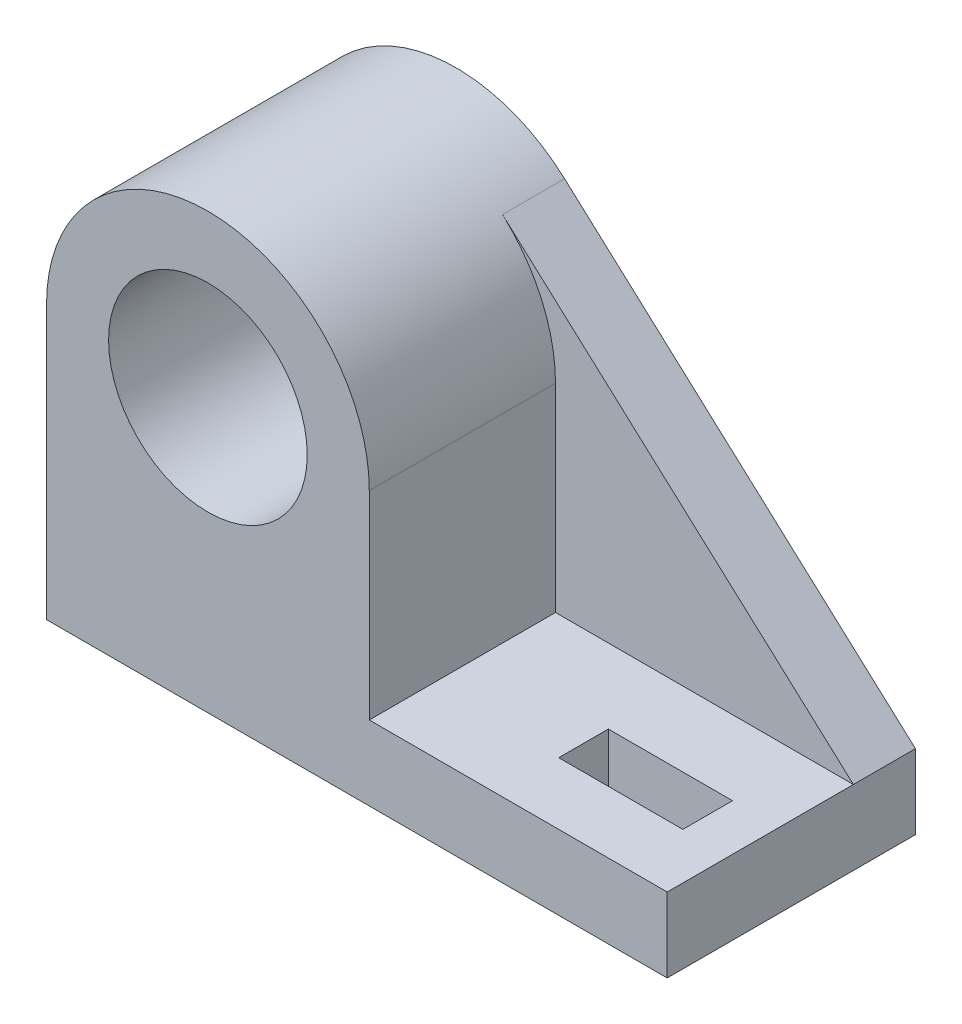
SolidWorks part; units mm, degrees
ref_plane "Front Plane" through (0, 0, 0) normal (0, 0, 1) x (1, 0, 0)
ref_plane "Top Plane" through (0, 0, 0) normal (0, 1, 0) x (1, 0, 0)
ref_plane "Right Plane" through (0, 0, 0) normal (1, 0, 0) x (0, 0, -1)
sketch "Sketch1" plane through (0, 0, 0) normal (0, 0, 1) x (1, 0, 0)
  line L0 (0, 64.0858) -> (0, -67.0709) construction
  line L1 (-108.5821, 0) -> (109.7015, 0) construction
  line L2 (-44.9627, 12) -> (-44.9627, 44)
  line L3 (-44.9627, 0) -> (55.0373, 0)
  line L4 (-44.9627, 0) -> (-44.9627, 12)
  line L5 (7.0373, 12) -> (55.0373, 12)
  line L6 (55.0373, 0) -> (55.0373, 12)
  line L7 (7.0373, 12) -> (7.0373, 44)
  arc A0 (-44.9627, 44) -> (7.0373, 44) centre (-18.9627, 44) cw
  circle A1 centre (-18.9627, 44) radius 16
  dimension "D1" = 100
  dimension "D2" = 12
  dimension "D3" = 32
  dimension "D4" = 32
  dimension "D5" = 52
extrude "Boss-Extrude1" add sketch "Sketch1" against normal blind 40
ref_plane "Plane1" through (0, 0, -40) normal (0, 0, 1) x (1, 0, 0)
sketch "Sketch5" plane through (0, 0, -40) normal (0, 0, 1) x (1, 0, 0)
  line L0 (55.0373, 12) -> (-1.4983, 63.2613)
  arc A0 (7.0373, 44) -> (-44.9627, 44) centre (-18.9627, 44) ccw construction
rib "Rib1" sketch "Sketch5" sketch "Sketch5" thickness 10 parameters "D1"=10
sketch "Sketch8" plane through (0, 12, 0) normal (0, 1, 0) x (1, 0, 0)
  line L4 (27.5596, 10) -> (47.5596, 10)
  line L5 (47.5596, 18) -> (47.5596, 10)
  line L9 (47.5596, 18) -> (27.5596, 18)
  line L10 (27.5596, 10) -> (27.5596, 18)
extrude "Cut-Extrude2" cut sketch "Sketch8" against normal blind 40
